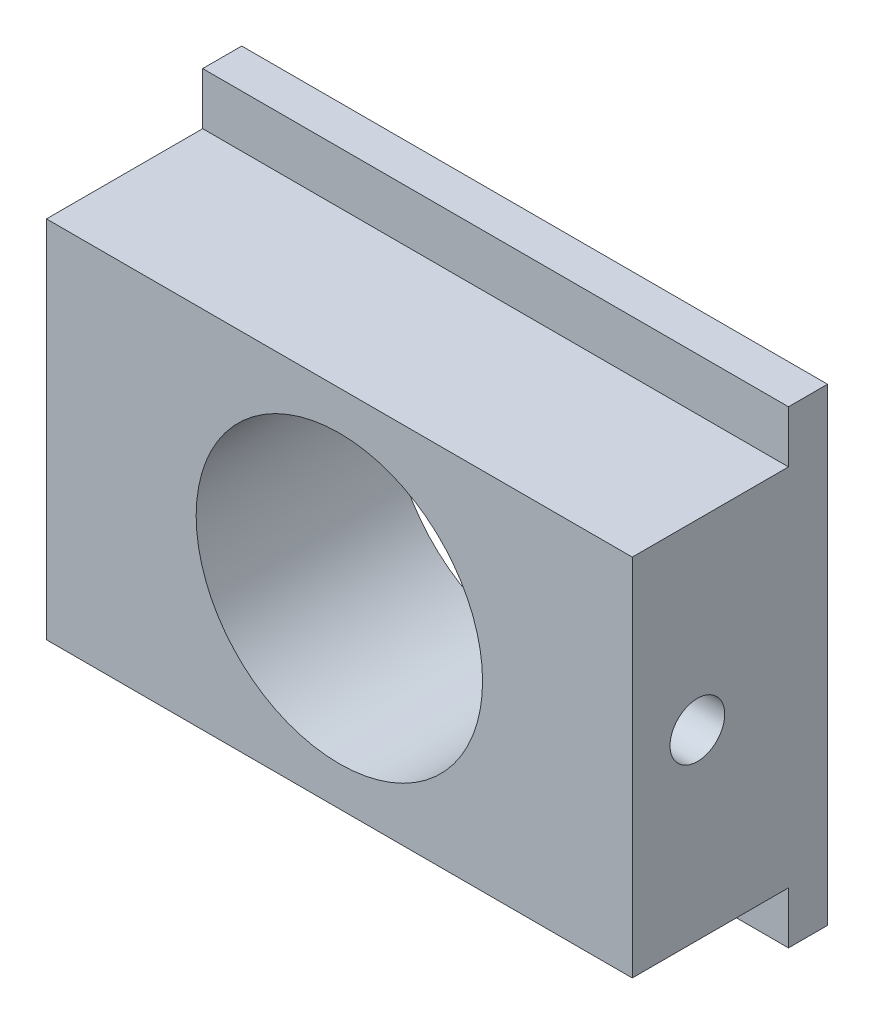
SolidWorks part; units mm, degrees
ref_plane "Front Plane" through (0, 0, 0) normal (0, 0, 1) x (1, 0, 0)
ref_plane "Top Plane" through (0, 0, 0) normal (0, 1, 0) x (1, 0, 0)
ref_plane "Right Plane" through (0, 0, 0) normal (1, 0, 0) x (0, 0, -1)
sketch "Sketch1" plane through (0, 0, 0) normal (0, 0, 1) x (1, 0, 0)
  line L1 (0, 0) -> (45, 0)
  line L2 (0, 0) -> (0, 28)
  line L3 (0, 28) -> (45, 28)
  line L4 (45, 0) -> (45, 28)
  circle A0 centre (22.5, 14) radius 11
  point P8 (0, 14)
  point P10 (22.5, 28)
  dimension "D2" = 22
  dimension "D1" = 28
  dimension "D3" = 45
extrude "Boss-Extrude1" add sketch "Sketch1" along normal blind 20
sketch "Sketch2" plane through (0, 0, 20) normal (0, 0, 1) x (1, 0, 0)
  line L1 (0, 0) -> (45, 0)
  line L2 (0, 0) -> (0, 28)
  line L3 (0, 28) -> (45, 28)
  line L4 (45, 0) -> (45, 28)
  circle A0 centre (22.5, 14) radius 6.25
  dimension "D1" = 12.5
hole_wizard "M5x0.8 Tapped Hole1" positions "3DSketch1" profile "Sketch3" tap size "M5x0.8" standard "ANSI Metric"
sketch3d "3DSketch1"
  line L1 (45, 0, 20) -> (45, 28, 20) construction
  line L2 (45, 0, 20) -> (45, 0, 0) construction
  point P0 (45, 14, 15)
  dimension "D1" = 5
  dimension "D2" = 14
cosmetic thread "Hole Thread1" parameters "D1"=8, "D2"=5
sketch "Sketch3" plane through (45, 14, 15) normal (0, 1, 0) x (0, 0, -1)
  line L0 (0, 0) -> (0, 9.2618)
  line L1 (0, 9.2618) -> (2.1, 8)
  line L2 (2.1, 8) -> (2.1, 0)
  line L5 (2.1, 0) -> (0, 0)
  line L10 (0, 9.2618) -> (-2.1, 8) construction
  line L11 (0, -6.35) -> (0, 107.95) construction
  dimension "Tap Drill Dia." = 4.2
  dimension "Tap Drill Depth" = 8
  dimension "Drill Angle" = 118
sketch "Sketch5" plane through (0, 0, 0) normal (0, 0, -1) x (-1, 0, 0)
  circle A0 centre (-22.5, 14) radius 11
  dimension "D1" = 22
sketch "Sketch6" plane through (0, 0, 0) normal (0, 0, -1) x (-1, 0, 0)
  line L1 (0, 0) -> (-45, 0)
  line L2 (0, 0) -> (0, 28)
  line L3 (0, 28) -> (-45, 28)
  line L4 (-45, 0) -> (-45, 28)
extrude "Cut-Extrude1" cut sketch "Sketch6" against normal blind 5
sketch "Sketch7" plane through (0, 0, 5) normal (0, 0, -1) x (-1, 0, 0)
  line L0 (0, 0) -> (0, 28) construction
  line L1 (-45, 28) -> (0, 28)
  line L2 (-45, 28) -> (-45, 32)
  line L3 (-45, 32) -> (0, 32)
  line L4 (0, 28) -> (0, 32)
  line L5 (0, 0) -> (-45, 0)
  line L6 (0, 0) -> (0, -4)
  line L7 (0, -4) -> (-45, -4)
  line L8 (-45, 0) -> (-45, -4)
  dimension "D1" = 4
  dimension "D2" = 4
extrude "Boss-Extrude5" add sketch "Sketch7" against normal blind 3
